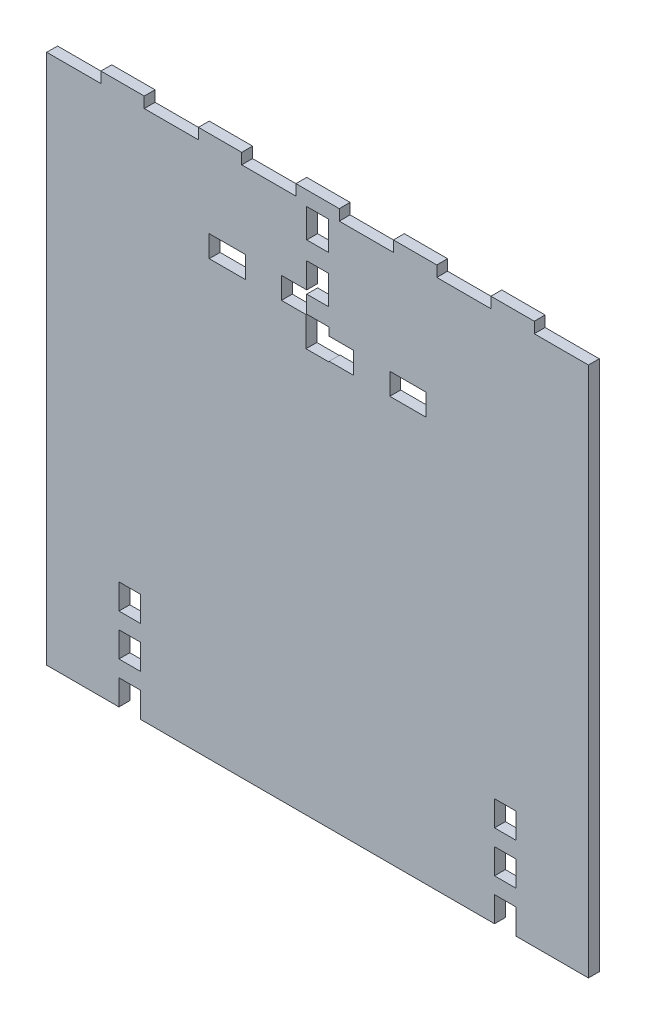
SolidWorks part; units mm, degrees
ref_plane "Plan de face" through (0, 0, 0) normal (0, 0, 1) x (1, 0, 0)
ref_plane "Plan de dessus" through (0, 0, 0) normal (0, 1, 0) x (1, 0, 0)
ref_plane "Plan de droite" through (0, 0, 0) normal (1, 0, 0) x (0, 0, -1)
sketch "Esquisse1" plane through (0, 0, 0) normal (0, 0, 1) x (1, 0, 0)
  line L1 (0, 0) -> (150, 0)
  line L2 (0, 0) -> (0, -150)
  line L3 (0, -150) -> (150, -150)
  line L4 (150, 0) -> (150, -150)
  dimension "D1" = 150
  dimension "D2" = 150
extrude "Boss.-Extru.1" add sketch "Esquisse1" along normal blind 3
sketch "Esquisse2" plane through (0, 0, 3) normal (0, 0, 1) x (1, 0, 0)
  line L0 (150, -150) -> (150, 0) construction
  line L1 (0, 0) -> (150, 0)
  line L2 (0, 0) -> (0, -3)
  line L3 (0, -3) -> (150, -3)
  line L4 (150, 0) -> (150, -3)
  dimension "D1" = 3
extrude "Boss.-Extru.2" [suppressed] add sketch "Esquisse2" along normal blind 80
sketch "Esquisse3" [suppressed] plane through (0, 0, 0) normal (0, 1, 0) x (1, 0, 0)
  line L0 (75, 0) -> (75, -83) construction
  line L1 (0, -83) -> (10, -83)
  line L2 (0, -83) -> (0, -73)
  line L3 (0, -73) -> (10, -73)
  line L4 (10, -83) -> (10, -73)
  line L5 (150, 0) -> (0, 0) construction
  line L6 (150, -83) -> (0, -83) construction
  line L7 (150, -83) -> (140, -83)
  line L8 (150, -83) -> (150, -73)
  line L9 (140, -83) -> (140, -73)
  line L10 (150, -73) -> (140, -73)
  dimension "D1" = 10
  dimension "D2" = 10
extrude "Enlèv. mat.-Extru.1" [suppressed] cut sketch "Esquisse3" against normal blind 80
sketch "Esquisse4" [suppressed] plane through (140, 0, 0) normal (1, 0, 0) x (0, 0, -1)
  line L0 (-78, 0) -> (-78, -3) construction
  line L1 (-73, 0) -> (-83, 0) construction
  line L2 (-73, -3) -> (-83, -3) construction
  line L3 (-83, -1.5) -> (-73, -1.5) construction
  line L4 (-83, 0) -> (-83, -3) construction
  line L5 (-73, -3) -> (-73, 0) construction
  circle A0 centre (-78, -1.5) radius 0.75
extrude "Boss.-Extru.3" [suppressed] add sketch "Esquisse4" along normal blind 5
sketch "Esquisse6" [suppressed] plane through (10, 0, 0) normal (-1, 0, 0) x (0, 0, 1)
  line L0 (78, 0) -> (78, -3) construction
  line L1 (83, 0) -> (73, 0) construction
  line L2 (83, -3) -> (73, -3) construction
  line L3 (73, -1.5) -> (83, -1.5) construction
  line L4 (73, -3) -> (73, 0) construction
  line L5 (83, -3) -> (83, 0) construction
  circle A0 centre (78, -1.5) radius 0.75
extrude "Boss.-Extru.5" [suppressed] add sketch "Esquisse6" along normal blind 5
sketch "Esquisse9" [suppressed] plane through (0, 0, 0) normal (0, 1, 0) x (1, 0, 0)
  line L0 (75, -83) -> (75, 0) construction
  line L1 (140, -83) -> (10, -83) construction
  line L2 (150, 0) -> (0, 0) construction
  line L3 (0, -36.5) -> (150, -36.5) construction
  line L4 (0, -73) -> (0, 0) construction
  line L5 (150, -73) -> (150, 0) construction
  line L6 (0, -3) -> (35, -33.5)
  line L7 (0, -70) -> (35, -39.5)
  line L8 (35, -33.5) -> (53, -33.5)
  line L9 (35, -39.5) -> (53, -39.5)
  line L10 (150, -70) -> (115, -39.5)
  line L11 (115, -39.5) -> (97, -39.5)
  line L12 (115, -33.5) -> (97, -33.5)
  line L13 (150, -3) -> (115, -33.5)
  line L14 (0, -70) -> (0, -73)
  line L15 (0, -73) -> (10, -73)
  line L16 (10, -83) -> (10, -73) construction
  line L17 (10, -73) -> (0, -73) construction
  line L18 (10, -73) -> (10, -83)
  line L19 (10, -83) -> (140, -83)
  line L20 (140, -83) -> (140, -73)
  line L21 (140, -73) -> (150, -73)
  line L22 (150, -73) -> (150, -70)
  line L23 (150, -3) -> (150, 0)
  line L24 (150, 0) -> (0, 0)
  line L25 (0, 0) -> (0, -3)
  circle A0 centre (61.4853, -36.5) radius 9
  circle A1 centre (88.5147, -36.5) radius 9
  point P12 (0, -3)
  line M6 (150, -73) -> (150, 0)
  line M8 (0, 0) -> (0, -73)
  dimension "D3" = 18
  dimension "D1" = 3
  dimension "D2" = 3
  dimension "D4" = 35
  dimension "D5" = 18
extrude "Enlèv. mat.-Extru.2" [suppressed] cut sketch "Esquisse9" against normal blind 3 contours A0 L8 L6 L7 L9 M8 | A0 | L12 A1 L11 L10 L13 M6 | A1 M8
sketch "Esquisse10" [suppressed] plane through (0, 0, 0) normal (-1, 0, 0) x (0, 0, 1)
  line L0 (3, -3) -> (3, -150) construction
  line L1 (3, 0) -> (33.5, 0) construction
  line L2 (0, -120) -> (0, -63)
  line L3 (0, 0) -> (0, -150) construction
  line L4 (0, -63) -> (60, -63)
  line L5 (60, -63) -> (60, -120)
  line L6 (60, -120) -> (0, -120)
  point P0 (3, -63)
  point P5 (3, -120)
  dimension "D1" = 63
  dimension "D2" = 120
  dimension "D3" = 60
extrude "Boss.-Extru.9" [suppressed] add sketch "Esquisse10" along normal blind 3
sketch "Esquisse11" [suppressed] plane through (150, 0, 0) normal (1, 0, 0) x (0, 0, -1)
  line L0 (0, -63) -> (-60, -63)
  line L1 (-60, -63) -> (-60, -120)
  line L2 (-60, -120) -> (0, -120)
  line L3 (0, -120) -> (0, -63)
extrude "Boss.-Extru.10" [suppressed] add sketch "Esquisse11" along normal blind 3
fillet "Congé1" [suppressed] radius 10
sketch "Esquisse12" plane through (0, 0, 0) normal (0, 0, -1) x (-1, 0, 0)
  line L0 (0, -150) -> (-150, -150) construction
  line L1 (-130, -120) -> (-124, -120)
  line L2 (-130, -120) -> (-130, -127)
  line L3 (-130, -127) -> (-124, -127)
  line L4 (-124, -120) -> (-124, -127)
  line L5 (-130, -131.5) -> (-124, -131.5)
  line L6 (-130, -131.5) -> (-130, -138.5)
  line L7 (-130, -138.5) -> (-124, -138.5)
  line L8 (-124, -131.5) -> (-124, -138.5)
  line L9 (-130, -143) -> (-124, -143)
  line L10 (-130, -143) -> (-130, -150)
  line L11 (-130, -150) -> (-124, -150)
  line L12 (-124, -143) -> (-124, -150)
  line L13 (-124, -150) -> (-124, -143) construction
  line L14 (-20, -143) -> (-26, -143) construction
  line L15 (-26, -120) -> (-20, -120)
  line L16 (-26, -120) -> (-26, -127)
  line L17 (-26, -127) -> (-20, -127)
  line L18 (-20, -120) -> (-20, -127)
  line L19 (-26, -131.5) -> (-20, -131.5)
  line L20 (-26, -131.5) -> (-26, -138.5)
  line L21 (-26, -138.5) -> (-20, -138.5)
  line L22 (-20, -131.5) -> (-20, -138.5)
  line L23 (-26, -143) -> (-20, -143)
  line L24 (-26, -143) -> (-26, -150)
  line L25 (-26, -150) -> (-20, -150)
  line L26 (-20, -143) -> (-20, -150)
extrude "Enlèv. mat.-Extru.3" cut sketch "Esquisse12" against normal blind 3
sketch "Esquisse14" plane through (0, 0, 0) normal (0, 0, -1) x (-1, 0, 0)
  line L0 (-150, 0) -> (0, 0) construction
  line L1 (-135, -3) -> (-150, -3)
  line L2 (-135, -3) -> (-135, 0)
  line L3 (-135, 0) -> (-150, 0)
  line L4 (-150, -3) -> (-150, 0)
  line L5 (-123, -3) -> (-108, -3)
  line L6 (-123, -3) -> (-123, 0)
  line L7 (-123, 0) -> (-108, 0)
  line L8 (-108, -3) -> (-108, 0)
  line L9 (-108, -3) -> (-108, 0) construction
  line L10 (-81, -3) -> (-81, 0) construction
  line L11 (-96, -3) -> (-81, -3)
  line L12 (-96, -3) -> (-96, 0)
  line L13 (-96, 0) -> (-81, 0)
  line L14 (-81, -3) -> (-81, 0)
  line L15 (-54, -3) -> (-54, 0) construction
  line L16 (-69, -3) -> (-54, -3)
  line L17 (-69, -3) -> (-69, 0)
  line L18 (-69, 0) -> (-54, 0)
  line L19 (-54, -3) -> (-54, 0)
  line L21 (-42, -3) -> (-27, -3)
  line L22 (-42, -3) -> (-42, 0)
  line L23 (-42, 0) -> (-27, 0)
  line L24 (-27, -3) -> (-27, 0)
  line L25 (-15, -3) -> (0, -3)
  line L26 (-15, -3) -> (-15, 0)
  line L27 (-15, 0) -> (0, 0)
  line L28 (0, -3) -> (0, 0)
extrude "Enlèv. mat.-Extru.4" cut sketch "Esquisse14" against normal blind 3
sketch "Esquisse15" plane through (0, 0, 0) normal (0, 0, -1) x (-1, 0, 0)
  line L0 (-72, -25) -> (-72, -30)
  line L1 (-105, -38) -> (-95, -38)
  line L2 (-105, -38) -> (-105, -32)
  line L3 (-105, -32) -> (-95, -32)
  line L4 (-95, -38) -> (-95, -32)
  line L5 (-85, -38) -> (-78, -38)
  line L6 (-85, -38) -> (-85, -32)
  line L7 (-85, -32) -> (-78, -32)
  line L10 (-72, -25) -> (-72, -30)
  line L11 (-78, -32) -> (-78, -38)
  line L12 (-72, -17) -> (-72, -24)
  line L13 (-65, -30) -> (-72, -30)
  line L14 (-65, -30) -> (-65, -24)
  line L15 (-65, -24) -> (-72, -24)
  line L17 (-78, -17) -> (-72, -17)
  line L18 (-78, -17) -> (-78, -25)
  line L19 (-78, -25) -> (-72, -25)
  line L21 (-78, -12) -> (-72, -12)
  line L22 (-78, -12) -> (-78, -4)
  line L23 (-78, -4) -> (-72, -4)
  line L24 (-72, -12) -> (-72, -4)
  line L25 (-55, -30) -> (-45, -30)
  line L26 (-55, -30) -> (-55, -24)
  line L27 (-55, -24) -> (-45, -24)
  line L28 (-45, -30) -> (-45, -24)
  line L29 (-72, -30) -> (-65, -30)
extrude "Enlèv. mat.-Extru.9" cut sketch "Esquisse15" against normal blind 10 contours L25 L28 L27 L26 | L18 L19 L0 L13 L14 L15 L12 L17 | L21 L24 L23 L22 | L11 L7 L6 L5 | L1 L4 L3 L2
sketch "Esquisse17" plane through (0, 0, 0) normal (0, 0, -1) x (-1, 0, 0)
  line L0 (-78, -38) -> (-72, -38) construction
  line L1 (-78.2, -38.2) -> (-71.8, -38.2)
  line L2 (-78.2, -38.2) -> (-78.2, -29.8)
  line L3 (-78.2, -29.8) -> (-71.8, -29.8)
  line L4 (-71.8, -38.2) -> (-71.8, -29.8)
  line L5 (-78, -30) -> (-72, -30) construction
  line L6 (-72, -30) -> (-72, -38) construction
  line L7 (-78, -32) -> (-78, -38) construction
  dimension "D1" = 0.2
  dimension "D2" = 0.2
  dimension "D3" = 0.2
  dimension "D4" = 0.2
extrude "Enlèv. mat.-Extru.12" cut sketch "Esquisse17" against normal blind 10
